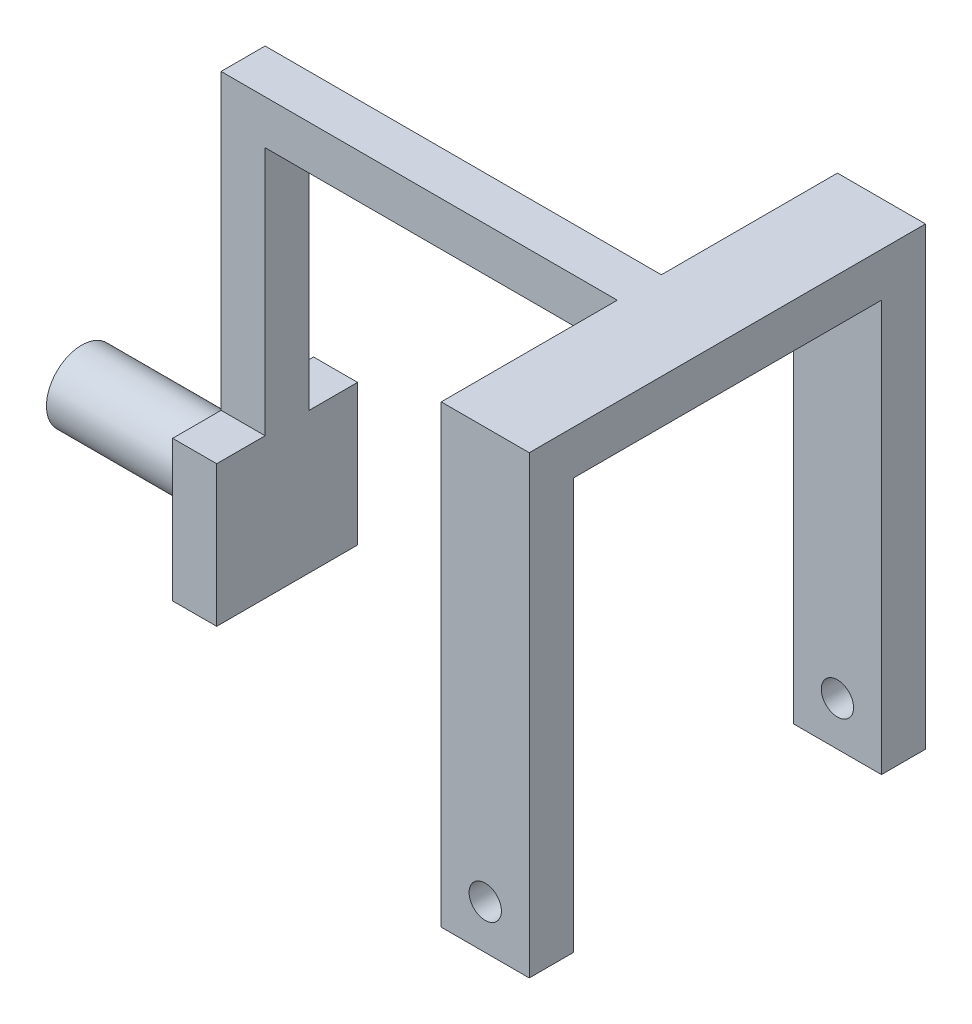
SolidWorks part; units mm, degrees
ref_plane "Front Plane" through (0, 0, 0) normal (0, 0, 1) x (1, 0, 0)
ref_plane "Top Plane" through (0, 0, 0) normal (0, 1, 0) x (1, 0, 0)
ref_plane "Right Plane" through (0, 0, 0) normal (1, 0, 0) x (0, 0, -1)
sketch "Sketch1" plane through (0, 0, 0) normal (1, 0, 0) x (0, 0, -1)
  circle A0 centre (0, 0) radius 12
  dimension "D1" = 24
extrude "Boss-Extrude1" add sketch "Sketch1" along normal blind 55
sketch "Sketch4" plane through (55, 0, 0) normal (1, 0, 0) x (0, 0, -1)
  line L1 (-24, -24) -> (24, -24)
  line L2 (-24, -24) -> (-24, 24)
  line L3 (-24, 24) -> (24, 24)
  line L4 (24, -24) -> (24, 24)
  line L5 (-24, -24) -> (24, 24) construction
  line L6 (-24, 24) -> (24, -24) construction
  point P0 (0, 0)
  dimension "D1" = 48
  dimension "D2" = 48
extrude "Boss-Extrude3" add sketch "Sketch4" along normal blind 15
sketch "Sketch5" plane through (0, 24, 0) normal (0, 1, 0) x (1, 0, 0)
  line L0 (70, 24) -> (70, -24) construction
  line L1 (55, -7.5) -> (70, -7.5)
  line L2 (55, -7.5) -> (55, 7.5)
  line L3 (55, 7.5) -> (70, 7.5)
  line L4 (70, -7.5) -> (70, 7.5)
  line L5 (55, -7.5) -> (70, 7.5) construction
  line L6 (55, 7.5) -> (70, -7.5) construction
  point P0 (62.5, 0)
  dimension "D1" = 15
extrude "Boss-Extrude4" add sketch "Sketch5" along normal blind 100
sketch "Sketch6" plane through (70, 0, 0) normal (1, 0, 0) x (0, 0, -1)
  line L1 (-7.5, 109) -> (7.5, 109)
  line L2 (-7.5, 109) -> (-7.5, 124)
  line L3 (-7.5, 124) -> (7.5, 124)
  line L4 (7.5, 109) -> (7.5, 124)
  line L5 (-7.5, 109) -> (7.5, 124) construction
  line L6 (-7.5, 124) -> (7.5, 109) construction
  point P0 (0, 116.5)
  dimension "D1" = 15
  dimension "D2" = 15
extrude "Boss-Extrude6" add sketch "Sketch6" along normal blind 150
sketch "Sketch7" plane through (0, 0, -7.5) normal (0, 0, -1) x (-1, 0, 0)
  line L0 (-220, 124) -> (-55, 124) construction
  line L1 (-220, 109) -> (-190, 109)
  line L2 (-220, 109) -> (-220, 124)
  line L3 (-220, 124) -> (-190, 124)
  line L4 (-190, 109) -> (-190, 124)
  line L5 (-220, 109) -> (-190, 124) construction
  line L6 (-220, 124) -> (-190, 109) construction
  line L8 (-220, 109) -> (-220, 124) construction
  point P0 (-205, 116.5)
  dimension "D1" = 15
  dimension "D2" = 30
  dimension "D3" = 0
extrude "Boss-Extrude7" add sketch "Sketch7" along normal blind 60 and the other way blind 75
sketch "Sketch8" plane through (0, 109, 0) normal (0, -1, 0) x (1, 0, 0)
  line L0 (220, 67.5) -> (220, -67.5) construction
  line L1 (190, -67.5) -> (220, -67.5)
  line L2 (190, -67.5) -> (190, -52.5)
  line L3 (190, -52.5) -> (220, -52.5)
  line L4 (220, -67.5) -> (220, -52.5)
  line L5 (190, -67.5) -> (220, -52.5) construction
  line L6 (190, -52.5) -> (220, -67.5) construction
  line L7 (220, 67.5) -> (190, 67.5) construction
  line L8 (190, 52.5) -> (220, 52.5)
  line L9 (190, 52.5) -> (190, 67.5)
  line L10 (190, 67.5) -> (220, 67.5)
  line L11 (220, 52.5) -> (220, 67.5)
  line L12 (190, 52.5) -> (220, 67.5) construction
  line L13 (190, 67.5) -> (220, 52.5) construction
  line L14 (220, -67.5) -> (190, -67.5) construction
  point P0 (205, -60)
  point P7 (205, 60)
  dimension "D1" = 30
  dimension "D2" = 15
  dimension "D3" = 7.5
  dimension "D4" = 30
  dimension "D5" = 15
  dimension "D6" = 7.5
extrude "Boss-Extrude8" add sketch "Sketch8" along normal blind 140
sketch "Sketch9" plane through (0, 0, 67.5) normal (0, 0, 1) x (1, 0, 0)
  line L0 (220, 124) -> (220, -31) construction
  line L1 (220, -31) -> (190, -31) construction
  circle A0 centre (205, -16) radius 5.5
  point P6 (205, -31)
  dimension "D1" = 11
  dimension "D2" = 15
  dimension "D3" = 15
extrude "Cut-Extrude1" cut sketch "Sketch9" against normal through all
